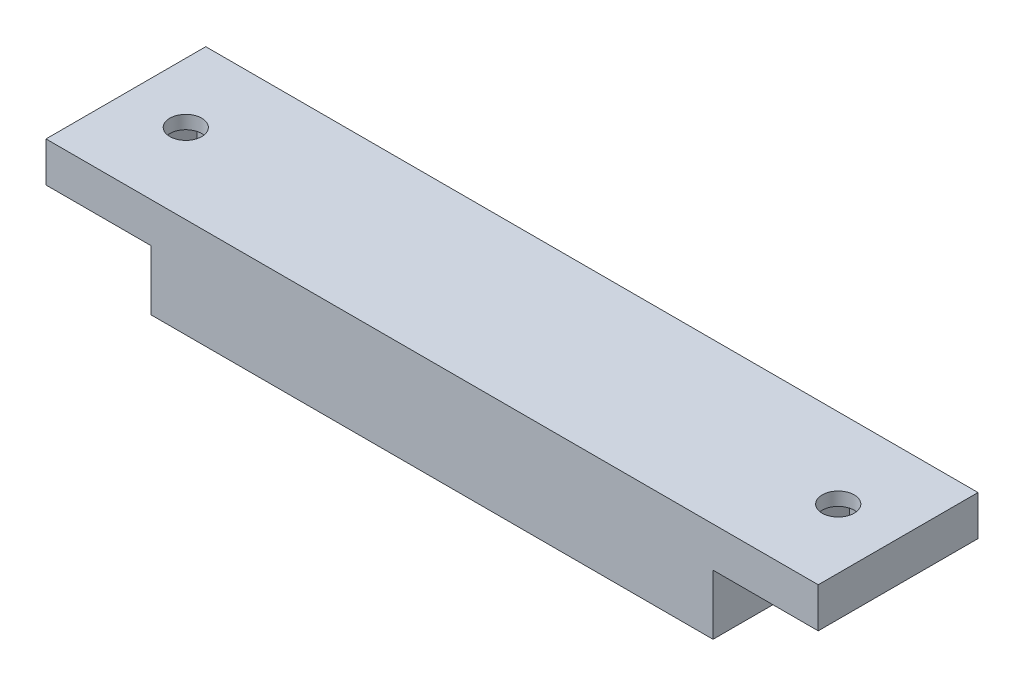
SolidWorks part; units mm, degrees
ref_plane "Front" through (0, 0, 0) normal (0, 0, 1) x (1, 0, 0)
ref_plane "Top" through (0, 0, 0) normal (0, 1, 0) x (1, 0, 0)
ref_plane "Right" through (0, 0, 0) normal (1, 0, 0) x (0, 0, -1)
sketch "草图1" plane through (0, 0, 0) normal (0, 1, 0) x (1, 0, 0)
  line L1 (-21.1, 6) -> (21.1, 6)
  line L2 (-21.1, 6) -> (-21.1, -6)
  line L3 (-21.1, -6) -> (21.1, -6)
  line L4 (21.1, 6) -> (21.1, -6)
  line L5 (-21.1, 6) -> (21.1, -6) construction
  line L6 (-21.1, -6) -> (21.1, 6) construction
  point P0 (0, 0)
  dimension "D1" = 42.2
  dimension "D2" = 12
extrude "凸台-拉伸1" add sketch "草图1" along normal blind 6
sketch "草图2" plane through (21.1, 0, 0) normal (1, 0, 0) x (0, 0, -1)
  line L0 (0, 0) -> (0, 6) construction
  line L1 (3.25, 3) -> (1.25, 0)
  line L2 (-3.25, 3) -> (3.25, 3)
  line L3 (-6, 6) -> (6, 6) construction
  line L4 (-1.25, 0) -> (1.25, 0)
  line L6 (-3.25, 6) -> (-3.25, 0) construction
  line L7 (-6, 0) -> (6, 0) construction
  line L8 (-3.25, 3) -> (-1.25, 0)
  dimension "D1" = 3.25
  dimension "D2" = 2
extrude "切除-拉伸1" cut sketch "草图2" against normal through all
sketch "草图3" plane through (0, 6, 0) normal (0, 1, 0) x (1, 0, 0)
  line L1 (-29, 6) -> (29, 6)
  line L2 (-29, 6) -> (-29, -6)
  line L3 (-29, -6) -> (29, -6)
  line L4 (29, 6) -> (29, -6)
  line L5 (-29, 6) -> (29, -6) construction
  line L6 (-29, -6) -> (29, 6) construction
  point P0 (0, 0)
  dimension "D1" = 58
extrude "凸台-拉伸2" add sketch "草图3" against normal mid plane 3
sketch "草图4" plane through (0, 4.5, 0) normal (0, -1, 0) x (1, 0, 0)
  line L0 (-21.1, -6) -> (-29, -6) construction
  line L1 (-22.1906, 0) -> (-23.3453, 2)
  line L2 (-23.3453, 2) -> (-25.6547, 2)
  line L3 (-25.6547, 2) -> (-26.8094, 0)
  line L4 (-26.8094, 0) -> (-25.6547, -2)
  line L5 (-25.6547, -2) -> (-23.3453, -2)
  line L6 (-23.3453, -2) -> (-22.1906, 0)
  line L8 (-29, -6) -> (-29, 6) construction
  line L9 (0, 6) -> (0, -6) construction
  line L10 (-21.1, 6) -> (21.1, 6) construction
  line L11 (21.1, -6) -> (-21.1, -6) construction
  line L12 (22.1906, 0) -> (23.3453, 2)
  line L13 (23.3453, -2) -> (22.1906, 0)
  line L14 (25.6547, -2) -> (23.3453, -2)
  line L15 (26.8094, 0) -> (25.6547, -2)
  line L16 (25.6547, 2) -> (26.8094, 0)
  line L17 (23.3453, 2) -> (25.6547, 2)
  circle A0 centre (-24.5, 0) radius 2 construction
  dimension "D1" = 6
  dimension "D2" = 4.5
extrude "切除-拉伸2" cut sketch "草图4" against normal blind 2
sketch "草图5" plane through (0, 6.5, 0) normal (0, -1, 0) x (1, 0, 0)
  circle A0 centre (-24.5, 0) radius 1.2
  circle A1 centre (24.5, 0) radius 1.2
  dimension "D1" = 2.4
extrude "切除-拉伸3" cut sketch "草图5" against normal up to next
